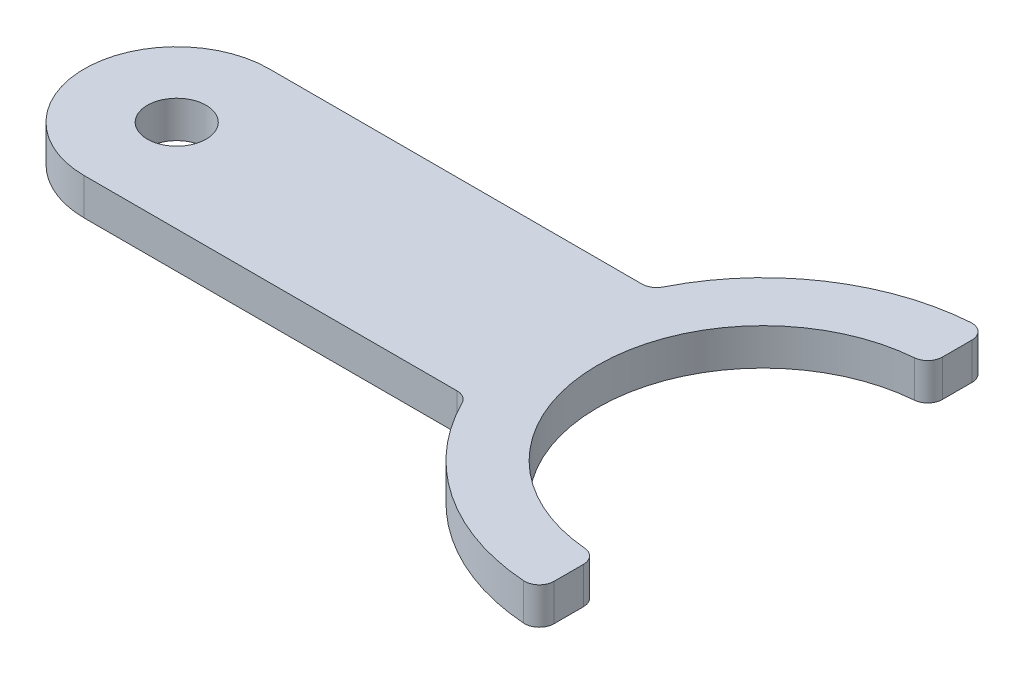
SolidWorks part; units mm, degrees
ref_plane "Front Plane" through (0, 0, 0) normal (0, 0, 1) x (1, 0, 0)
ref_plane "Top Plane" through (0, 0, 0) normal (0, 1, 0) x (1, 0, 0)
ref_plane "Right Plane" through (0, 0, 0) normal (1, 0, 0) x (0, 0, -1)
sketch "Sketch1" plane through (0, 0, 0) normal (0, 1, 0) x (1, 0, 0)
  line L0 (0, 12.5805) -> (50.7143, 12.5805)
  line L1 (0, -12.5805) -> (50.7143, -12.5805)
  line L2 (79.756, 28.426) -> (79.756, 24.4182)
  line L3 (79.756, -28.426) -> (79.756, -24.4182)
  circle A0 centre (0, 0) radius 4
  arc A1 (77.9193, 22.4249) -> (77.9193, -22.4249) centre (79.756, 0) ccw
  arc A2 (0, -12.5805) -> (0, 12.5805) centre (0, 0) cw
  arc A3 (77.6156, 30.4211) -> (52.5017, 13.6831) centre (79.756, 0) ccw
  arc A4 (52.5017, -13.6831) -> (77.6156, -30.4211) centre (79.756, 0) ccw
  arc A5 (79.756, -24.4182) -> (77.9193, -22.4249) centre (77.756, -24.4182) ccw
  arc A6 (77.6156, -30.4211) -> (79.756, -28.426) centre (77.756, -28.426) ccw
  arc A7 (50.7143, -12.5805) -> (52.5017, -13.6831) centre (50.7143, -14.5805) cw
  arc A8 (50.7143, 12.5805) -> (52.5017, 13.6831) centre (50.7143, 14.5805) ccw
  arc A9 (79.756, 24.4182) -> (77.9193, 22.4249) centre (77.756, 24.4182) cw
  arc A10 (77.6156, 30.4211) -> (79.756, 28.426) centre (77.756, 28.426) cw
  point P11 (79.756, -22.5)
  point P19 (51.9755, -12.5805)
  point P22 (51.9755, 12.5805)
  point P25 (79.756, 22.5)
  dimension "D1" = 8
  dimension "D3" = 45
  dimension "D4" = 2
  dimension "D2" = 79.756
extrude "Boss-Extrude1" add sketch "Sketch1" along normal blind 5
